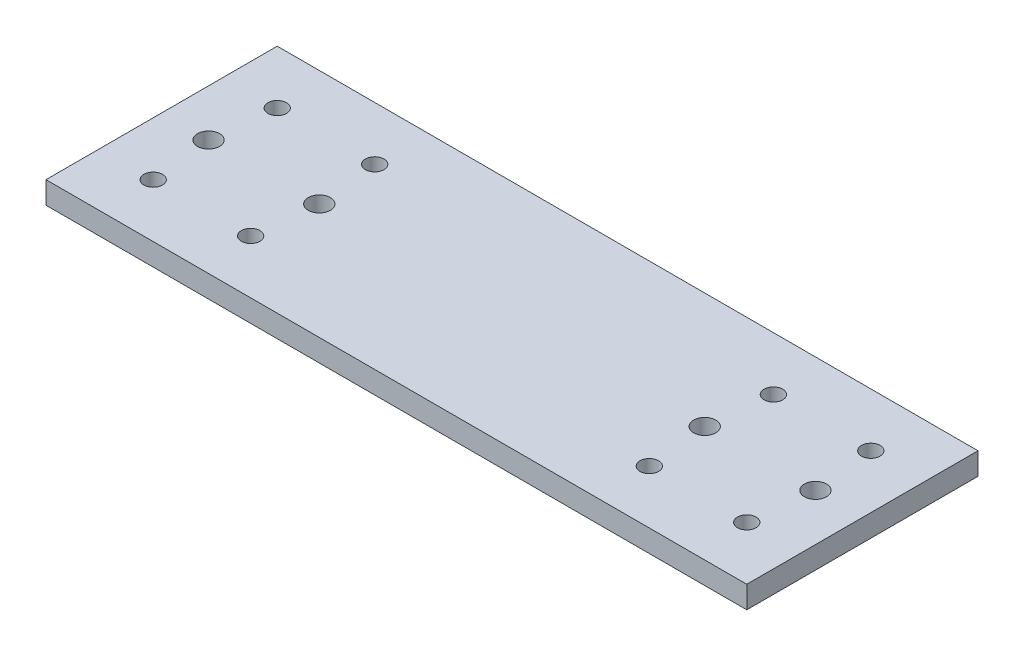
SolidWorks part; units mm, degrees
ref_plane "Front Plane" through (0, 0, 0) normal (0, 0, 1) x (1, 0, 0)
ref_plane "Top Plane" through (0, 0, 0) normal (0, 1, 0) x (1, 0, 0)
ref_plane "Right Plane" through (0, 0, 0) normal (1, 0, 0) x (0, 0, -1)
sketch "Sketch1" plane through (0, 0, 0) normal (0, 1, 0) x (1, 0, 0)
  line L0 (0, 0) -> (112, 0)
  line L1 (56, 0) -> (56, 14)
  line L2 (-23.1, 14) -> (-23.1, -14)
  line L3 (-11, 26.1) -> (123, 26.1)
  line L4 (-11, -26.1) -> (123, -26.1)
  line L5 (135.1, 14) -> (135.1, -14)
  line L7 (-23.1, 26.1) -> (135.1, 26.1)
  line L8 (-23.1, 26.1) -> (-23.1, -26.1)
  line L9 (-23.1, -26.1) -> (135.1, -26.1)
  line L10 (135.1, 26.1) -> (135.1, -26.1)
  circle A0 centre (-11, 14) radius 2.1
  circle A1 centre (11, 14) radius 2.1
  circle A2 centre (11, -14) radius 2.1
  circle A3 centre (-11, -14) radius 2.1
  circle A5 centre (123, -14) radius 2.1
  circle A6 centre (101, -14) radius 2.1
  circle A7 centre (101, 14) radius 2.1
  circle A8 centre (123, 14) radius 2.1
extrude "Boss-Extrude1" add sketch "Sketch1" along normal blind 5
sketch "Sketch2" plane through (0, 5, 0) normal (0, 1, 0) x (1, 0, 0)
  line L0 (56, 26.1) -> (56, 17.3464)
  line L1 (56, 26.1) -> (56, 21.4234)
  line L2 (-23.1, 26.1) -> (135.1, 26.1) construction
  circle A0 centre (-12.5, 0) radius 2.5
  circle A1 centre (12.5, 0) radius 2.5
  circle A2 centre (99.5, 0) radius 2.5
  circle A3 centre (124.5, 0) radius 2.5
extrude "Cut-Extrude1" cut sketch "Sketch2" against normal blind 10 contours A1 | A0 | A2 | A3
